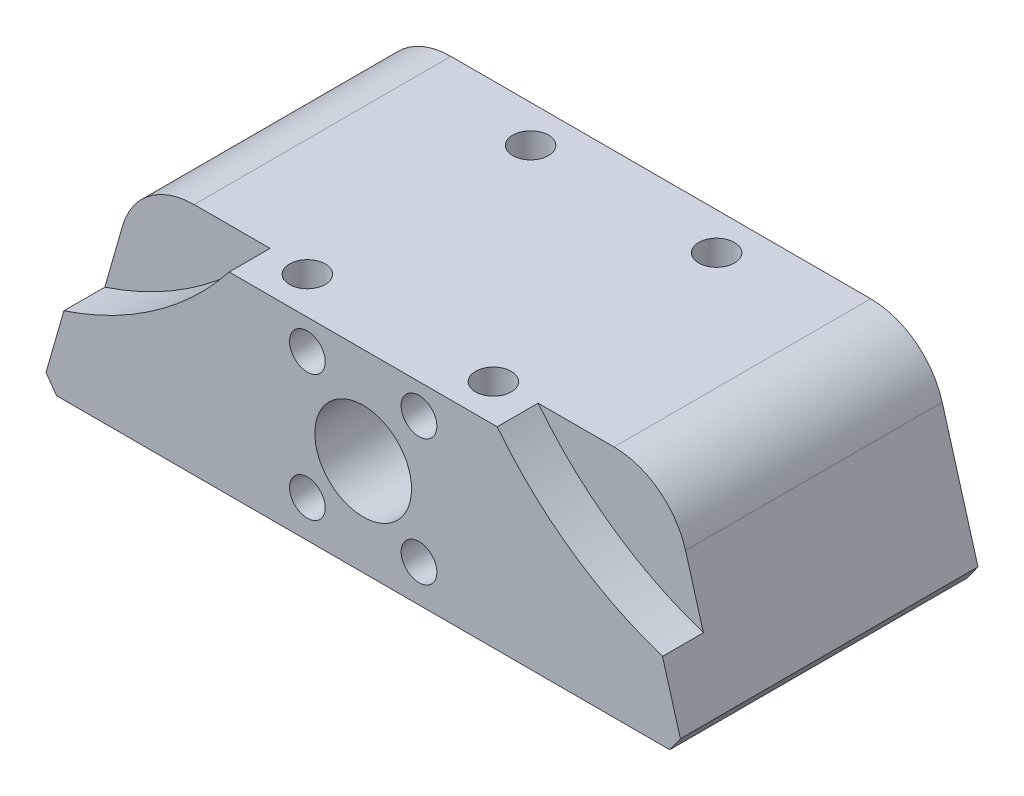
SolidWorks part; units mm, degrees
material "ABS"
ref_plane "前视基准面" through (0, 0, 0) normal (0, 0, 1) x (1, 0, 0)
ref_plane "上视基准面" through (0, 0, 0) normal (0, 1, 0) x (1, 0, 0)
ref_plane "右视基准面" through (0, 0, 0) normal (1, 0, 0) x (0, 0, -1)
sketch "草图1" plane through (0, 0, 0) normal (0, 0, 1) x (1, 0, 0)
  line L0 (-47.5, 50) -> (62.5, 50) construction
  line L1 (0, 0) -> (15, 0) construction
  line L2 (0, 0) -> (0, 17) construction
  line L3 (0, 17) -> (15, 17) construction
  line L4 (15, 0) -> (15, 17) construction
  line L9 (7.5, 21) -> (7.5, -5) construction
  line L10 (-35.7031, -5) -> (50.7031, -5)
  line L12 (-28.2477, 21) -> (43.2477, 21)
  line L14 (-28.2477, 21) -> (-35.7031, -5)
  line L15 (43.2477, 21) -> (50.7031, -5)
  circle A0 centre (15, 17) radius 2.4
  circle A1 centre (15, 0) radius 2.4
  circle A2 centre (0, 0) radius 2.4
  circle A3 centre (0, 17) radius 2.4
  circle A4 centre (-47.5, 50) radius 26.5 construction
  circle A5 centre (62.5, 50) radius 26.5 construction
  circle A6 centre (7.5, 8) radius 6.5
  point P23 (7.5, 17)
  dimension "D3" = 4.8
  dimension "D4" = 53
  dimension "D10" = 13
  dimension "D1" = 17
  dimension "D2" = 15
  dimension "D5" = 106
  dimension "D6" = 55
  dimension "D7" = 5
  dimension "D8" = 4
  dimension "D9" = 29
  dimension "D11" = 26
extrude "凸台-拉伸1" add sketch "草图1" along normal blind 40
fillet "圆角1" radius 10 2 edges at (43.2477, 21, 20) (-28.2477, 21, 20)
sketch "草图2" plane through (0, 21, 0) normal (0, 1, 0) x (1, 0, 0)
  line L0 (7.5, 0) -> (7.5, -40) construction
  line L1 (-5, -5) -> (20, -5) construction
  line L2 (-5, -5) -> (-5, -35) construction
  line L3 (-5, -35) -> (20, -35) construction
  line L4 (20, -5) -> (20, -35) construction
  line L5 (35.7121, 0) -> (-20.7121, 0) construction
  line L6 (35.7121, -40) -> (-20.7121, -40) construction
  circle A0 centre (-5, -5) radius 2.4
  circle A1 centre (20, -5) radius 2.4
  circle A2 centre (-5, -35) radius 2.4
  circle A3 centre (20, -35) radius 2.4
  point P10 (7.5, -5)
  dimension "D4" = 4.8
  dimension "D1" = 25
  dimension "D2" = 30
  dimension "D3" = 5
extrude "切除-拉伸1" cut sketch "草图2" against normal through all
sketch "草图4" plane through (0, 0, 40) normal (0, 0, 1) x (1, 0, 0)
  line L0 (-47.5, 50) -> (62.5, 50) construction
  line L1 (7.5, 8) -> (7.5, 50) construction
  line L2 (35.7121, 21) -> (-20.7121, 21) construction
  circle A0 centre (-47.5, 50) radius 47
  circle A1 centre (62.5, 50) radius 47
  point P5 (7.5, 50)
  dimension "D3" = 94
  dimension "D1" = 29
  dimension "D2" = 110
extrude "切除-拉伸2" cut sketch "草图4" against normal blind 5.5
sketch "草图5" plane through (0, 0, 0) normal (0, 0, -1) x (-1, 0, 0)
  line L0 (-48.7031, -5) -> (-50.7031, -5)
  line L1 (35.7031, -5) -> (-50.7031, -5) construction
  line L2 (-50.7031, -5) -> (-50.1296, -3)
  line L3 (-50.7031, -5) -> (-45.3248, 13.7564) construction
  line L4 (-50.1296, -3) -> (-48.7031, -5)
  line L5 (-7.5, 21) -> (-7.5, -5) construction
  line L6 (-35.7121, 21) -> (20.7121, 21) construction
  line L7 (35.1296, -3) -> (33.7031, -5)
  line L8 (35.7031, -5) -> (35.1296, -3)
  line L9 (33.7031, -5) -> (35.7031, -5)
  dimension "D1" = 2
  dimension "D2" = 2
extrude "切除-拉伸3" cut sketch "草图5" against normal through all
